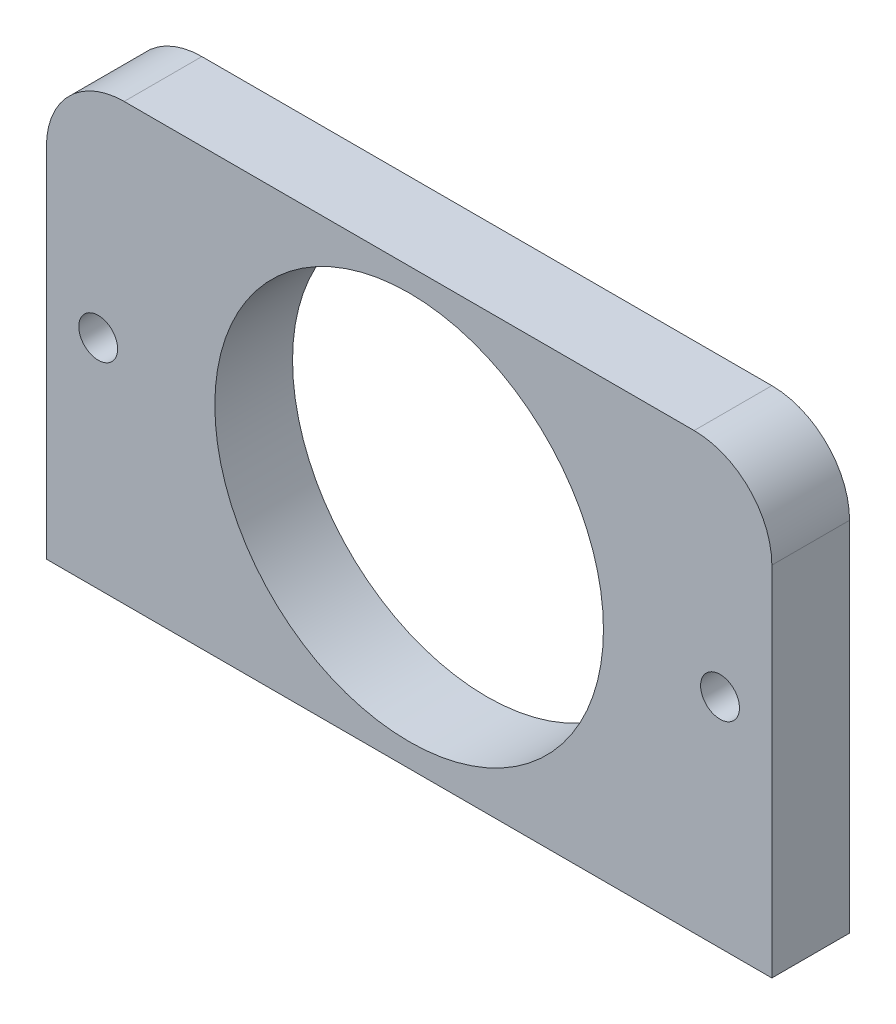
SolidWorks part; units mm, degrees
ref_plane "Front Plane" through (0, 0, 0) normal (0, 0, 1) x (1, 0, 0)
ref_plane "Top Plane" through (0, 0, 0) normal (0, 1, 0) x (1, 0, 0)
ref_plane "Right Plane" through (0, 0, 0) normal (1, 0, 0) x (0, 0, -1)
sketch "Sketch1" plane through (0, 0, 0) normal (0, 0, 1) x (1, 0, 0)
  line L0 (0, 0) -> (-60, 0) construction
  line L1 (-70, -42) -> (70, -42)
  line L2 (-70, -42) -> (-70, 27)
  line L3 (-55, 42) -> (55, 42)
  line L4 (70, -42) -> (70, 27)
  line L5 (-70, -42) -> (70, 42) construction
  line L6 (-70, 42) -> (70, -42) construction
  line L7 (0, 0) -> (0, 23.9904) construction
  circle A0 centre (0, 0) radius 37.5
  arc A1 (55, 42) -> (70, 27) centre (55, 27) cw
  arc A2 (-70, 27) -> (-55, 42) centre (-55, 27) cw
  circle A3 centre (-60, 0) radius 3.75
  circle A4 centre (60, 0) radius 3.75
  point P0 (0, 0)
  dimension "D1" = 75
  dimension "D4" = 15
  dimension "D6" = 7.5
  dimension "D2" = 42
  dimension "D3" = 140
  dimension "D5" = 60
extrude "Boss-Extrude1" add sketch "Sketch1" along normal blind 15
